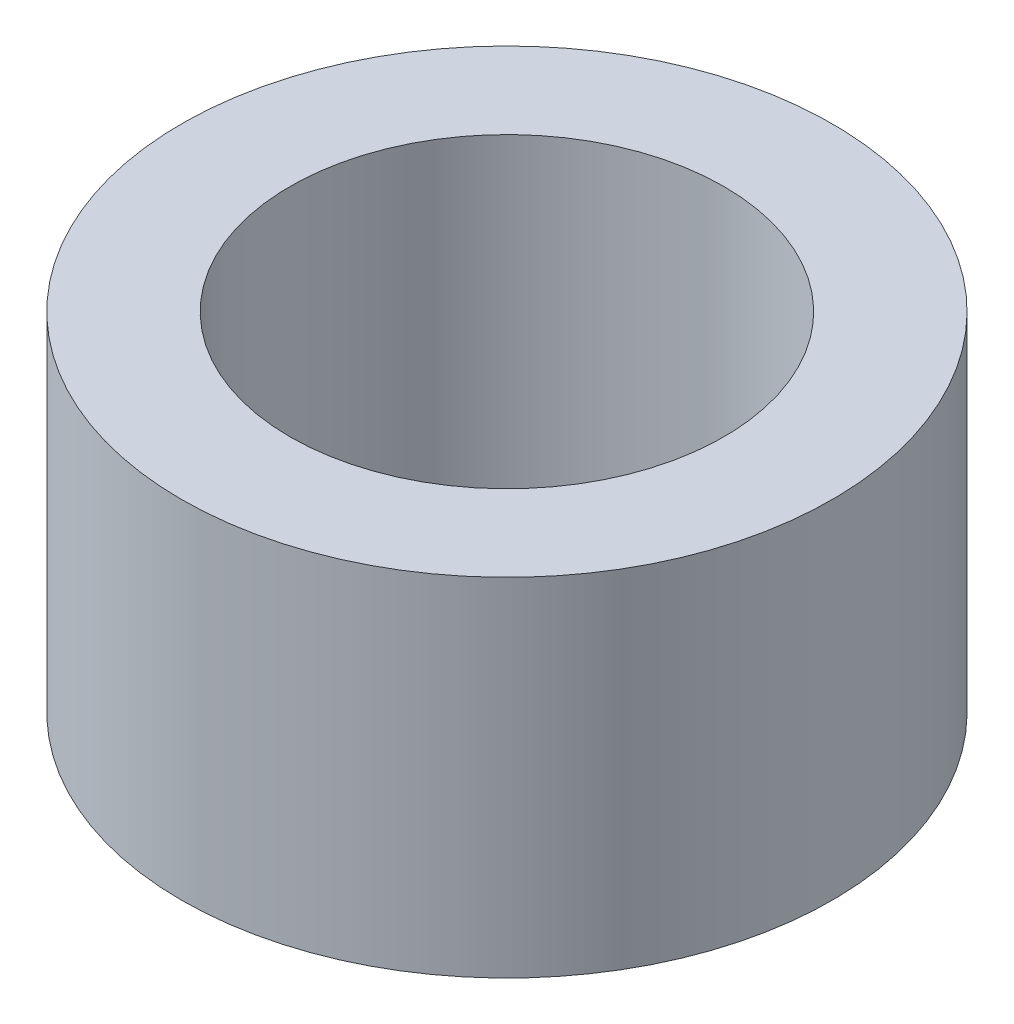
SolidWorks part; units mm, degrees
ref_plane "前视基准面" through (0, 0, 0) normal (0, 0, 1) x (1, 0, 0)
ref_plane "上视基准面" through (0, 0, 0) normal (0, 1, 0) x (1, 0, 0)
ref_plane "右视基准面" through (0, 0, 0) normal (1, 0, 0) x (0, 0, -1)
other "Configuration Table"
sketch "草图1" plane through (0, 0, 0) normal (0, 1, 0) x (1, 0, 0)
  circle A0 centre (0, 0) radius 5
  circle A1 centre (0, 0) radius 7.5
  dimension "D1" = 10
  dimension "D2" = 15
extrude "凸台-拉伸1" add sketch "草图1" along normal blind 8
